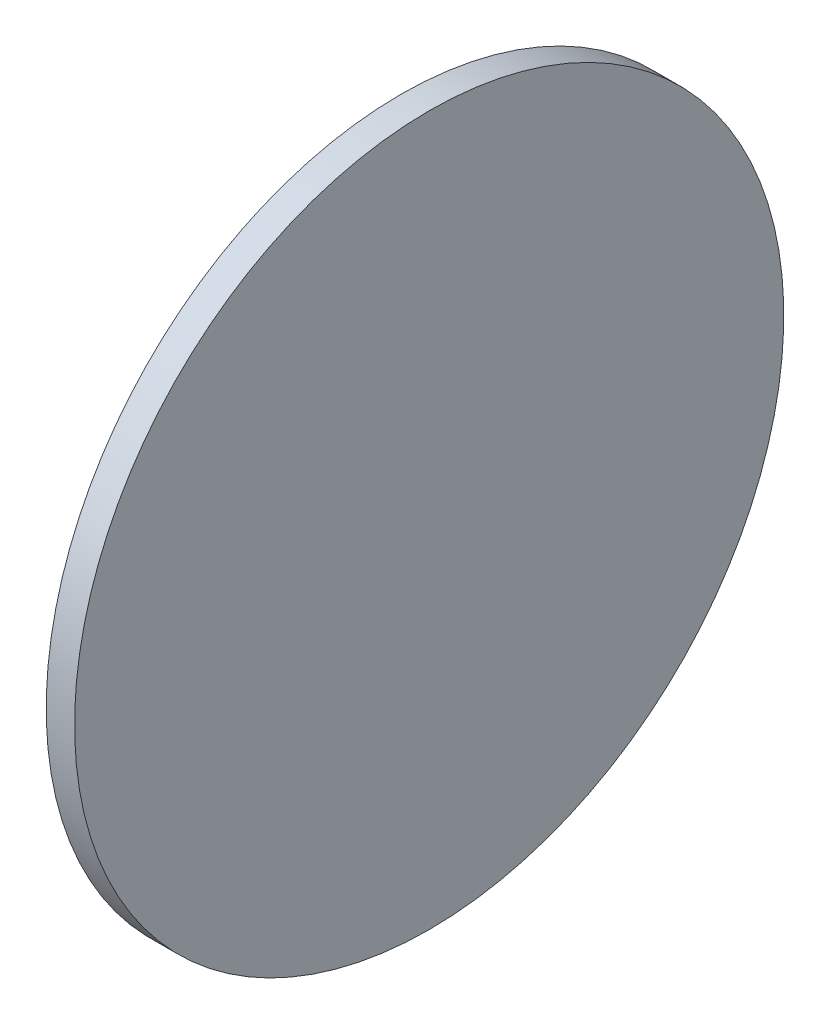
SolidWorks part; units mm, degrees
ref_plane "前视基准面" through (0, 0, 0) normal (0, 0, 1) x (1, 0, 0)
ref_plane "上视基准面" through (0, 0, 0) normal (0, 1, 0) x (1, 0, 0)
ref_plane "右视基准面" through (0, 0, 0) normal (1, 0, 0) x (0, 0, -1)
sketch "草图1" plane through (0, 0, 0) normal (0, 0, 1) x (1, 0, 0)
  line L0 (0, 0) -> (0, 31.0364)
  line L1 (0, 0) -> (53.0603, 0) construction
  line L2 (-9.5, 20.7056) -> (-9.5, 0) construction
  line L3 (0, 27.5) -> (-2.2, 27.5)
  line L4 (0, 0) -> (-9.5, 0)
  circle A0 centre (45.9479, 0) radius 55.4479
  dimension "D1" = 9.5
  dimension "D2" = 27.5
  dimension "D3" = 2.2
revolve "旋转1" add sketch "草图1" angle 360 about L4
